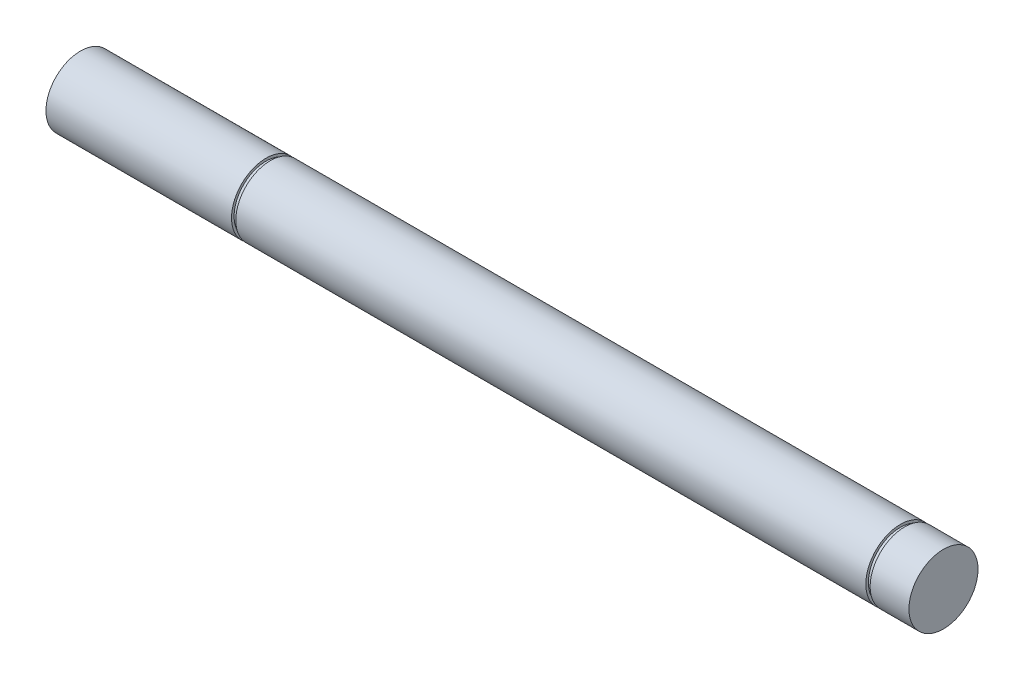
SolidWorks part; units mm, degrees
ref_plane "Front Plane" through (0, 0, 0) normal (0, 0, 1) x (1, 0, 0)
ref_plane "Top Plane" through (0, 0, 0) normal (0, 1, 0) x (1, 0, 0)
ref_plane "Right Plane" through (0, 0, 0) normal (1, 0, 0) x (0, 0, -1)
sketch "Sketch1" plane through (0, 0, 0) normal (1, 0, 0) x (0, 0, -1)
  circle A0 centre (0, 0) radius 4
  dimension "D1" = 8
extrude "Boss-Extrude1" add sketch "Sketch1" along normal mid plane 100
sketch "Sketch2" plane through (0, 0, 0) normal (0, 0, 1) x (1, 0, 0)
  line L0 (0, 0) -> (50, 0) construction
  line L5 (50, 4) -> (-50, 4) construction
  line L6 (45, 4) -> (45.5, 4)
  line L7 (50, -4) -> (50, 4) construction
  line L8 (45, 4) -> (45, 3.7)
  line L9 (45, 3.7) -> (45.5, 3.7)
  line L10 (45.5, 4) -> (45.5, 3.7)
  line L11 (45.25, 3.7) -> (45.25, 4) construction
  line L12 (45, 3.85) -> (45.5, 3.85) construction
  point P117 (45.25, 3.85)
  dimension "D1" = 0.5
  dimension "D2" = 7.4
  dimension "D3" = 5
revolve "Cut-Revolve1" cut sketch "Sketch2" angle 360 about L0
sketch "Sketch3" plane through (0, 0, 0) normal (0, 0, 1) x (1, 0, 0)
  line L0 (0, 0) -> (-50, 0) construction
  line L1 (-50, 4) -> (-50, -4) construction
  line L2 (45, 4) -> (-50, 4) construction
  line L3 (-28.5, 4) -> (-28, 4)
  line L4 (-28.5, 4) -> (-28.5, 3.7)
  line L5 (-28.5, 3.7) -> (-28, 3.7)
  line L6 (-28, 4) -> (-28, 3.7)
  line L7 (-28.25, 3.7) -> (-28.25, 4) construction
  line L8 (-28.5, 3.85) -> (-28, 3.85) construction
  point P49 (-28.25, 3.85)
  dimension "D1" = 7.4
  dimension "D2" = 0.5
  dimension "D3" = 22
revolve "Cut-Revolve2" cut sketch "Sketch3" angle 360 about L0
